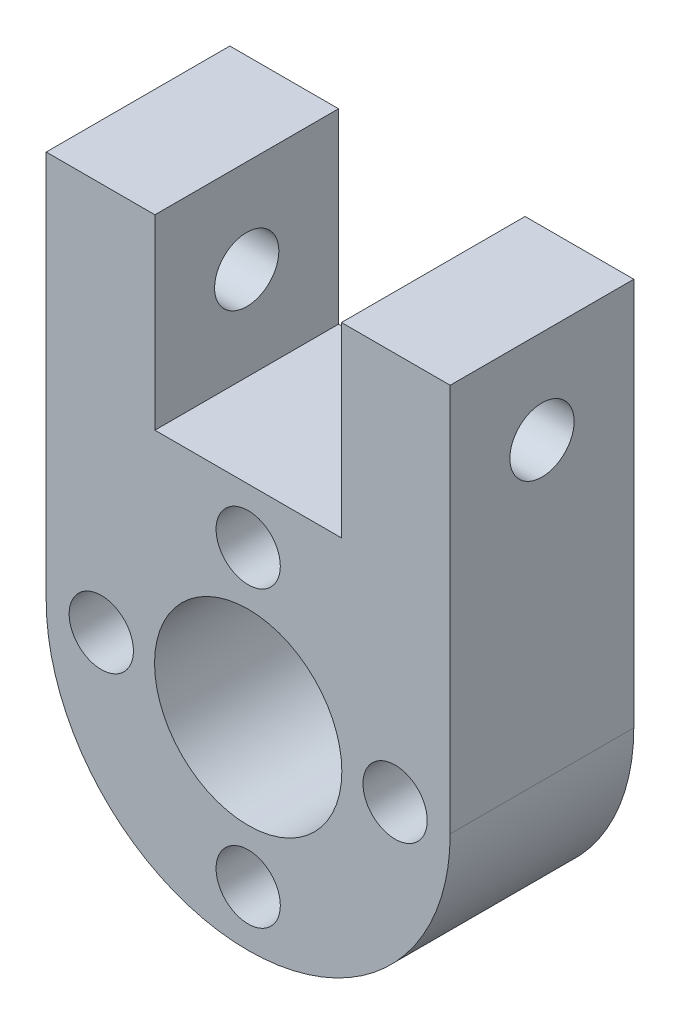
SolidWorks part; units mm, degrees
material "ABS PC"
ref_plane "Front Plane" through (0, 0, 0) normal (0, 0, 1) x (1, 0, 0)
ref_plane "Top Plane" through (0, 0, 0) normal (0, 1, 0) x (1, 0, 0)
ref_plane "Right Plane" through (0, 0, 0) normal (1, 0, 0) x (0, 0, -1)
sketch "Sketch1" plane through (0, 0, 0) normal (0, 0, 1) x (1, 0, 0)
  circle A0 centre (0, 0) radius 5.1
  circle A1 centre (0, 0) radius 11
  dimension "D1" = 22
  dimension "D2" = 10.2
extrude "Boss-Extrude1" add sketch "Sketch1" along normal blind 10
sketch "Sketch2" plane through (0, 0, 10) normal (0, 0, 1) x (1, 0, 0)
  circle A0 centre (0, 8) radius 1.75
  circle A1 centre (0, 0) radius 11
  circle A2 centre (0, 0) radius 11
  circle A3 centre (0, 0) radius 11
  circle A4 centre (8, 0) radius 1.75
  circle A5 centre (0, 0) radius 11
  circle A6 centre (0, -8) radius 1.75
  circle A7 centre (0, 0) radius 11
  circle A8 centre (-8, 0) radius 1.75
  point P17 (0, 0)
  dimension "D2" = 3.5
  dimension "D3" = 8
  dimension "D1" = 0
  dimension "D4" = 4
extrude "Cut-Extrude1" cut sketch "Sketch2" against normal through all contours A0 | A8 | A4 | A6
sketch "Sketch3" plane through (0, 0, 0) normal (0, 1, 0) x (1, 0, 0)
  line L1 (-11, 0) -> (11, 0)
  line L2 (-11, 0) -> (-11, -10)
  line L3 (-11, -10) -> (11, -10)
  line L4 (11, 0) -> (11, -10)
extrude "Boss-Extrude2" add sketch "Sketch3" along normal blind 10.16 from offset 11 separate body contours L2 L1 L4 L3
sketch "Sketch5" plane through (0, 11, 0) normal (0, -1, 0) x (1, 0, 0)
  line L4 (11, 10) -> (-11, 10)
  line L5 (-11, 10) -> (-11, 0)
  line L6 (-11, 0) -> (11, 0)
  line L7 (11, 0) -> (11, 10)
  line L8 (11, 10) -> (-11, 10)
  line L9 (-11, 10) -> (-11, 0)
  line L10 (-11, 0) -> (11, 0)
  line L11 (11, 0) -> (11, 10)
  dimension "D1" = 0
extrude "Boss-Extrude3" add sketch "Sketch5" along normal up to surface (11 mm away)
sketch "Sketch6" plane through (0, 0, 10) normal (0, 0, 1) x (1, 0, 0)
  line L0 (-11, 21.16) -> (11, 21.16) construction
  line L1 (-5.08, 21.16) -> (5.08, 21.16)
  line L2 (-5.08, 21.16) -> (-5.08, 11)
  line L3 (-5.08, 11) -> (5.08, 11)
  line L4 (5.08, 21.16) -> (5.08, 11)
  point P6 (0, 21.16)
  point P7 (0, 21.16)
  dimension "D1" = 10.16
  dimension "D2" = 10.16
extrude "Cut-Extrude2" cut sketch "Sketch6" against normal through all
sketch "Sketch7" plane through (11, 0, 0) normal (1, 0, 0) x (0, 0, -1)
  line L0 (-10, 14.796) -> (0, 14.796) construction
  line L1 (-10, 21.16) -> (-10, 0) construction
  line L2 (0, 21.16) -> (0, 0) construction
  line L3 (0, 21.16) -> (-10, 21.16) construction
  circle A0 centre (-5, 16.08) radius 1.75
  point P10 (-5, 14.796)
  dimension "D1" = 3.5
  dimension "D2" = 6.364
  dimension "D3" = 5.08
extrude "Cut-Extrude3" cut sketch "Sketch7" against normal through all
